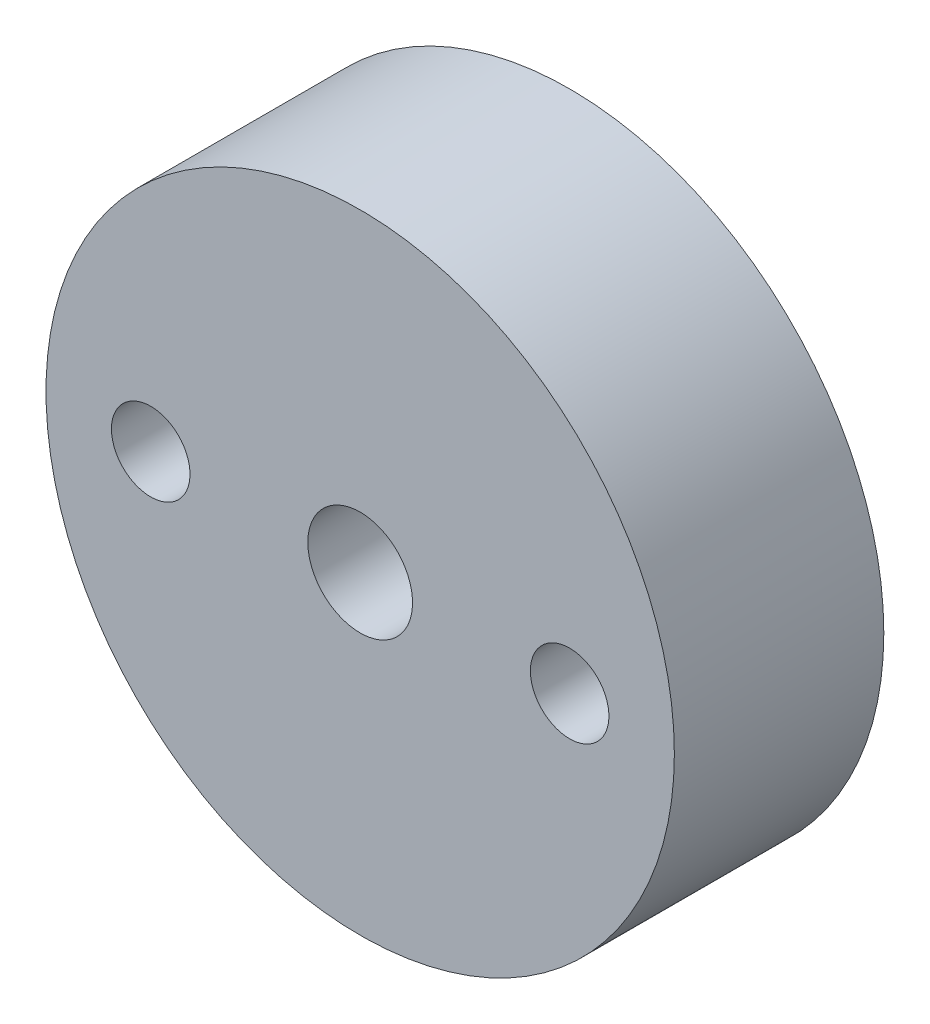
SolidWorks part; units mm, degrees
ref_plane "Front Plane" through (0, 0, 0) normal (0, 0, 1) x (1, 0, 0)
ref_plane "Top Plane" through (0, 0, 0) normal (0, 1, 0) x (1, 0, 0)
ref_plane "Right Plane" through (0, 0, 0) normal (1, 0, 0) x (0, 0, -1)
sketch "Sketch1" plane through (0, 0, 0) normal (0, 0, 1) x (1, 0, 0)
  circle A0 centre (0, 0) radius 38.1
  dimension "D1" = 76.2
extrude "OD Don't Care" add sketch "Sketch1" along normal blind 25.4
sketch "Sketch2" plane through (0, 0, 0) normal (0, 0, -1) x (-1, 0, 0)
  line L0 (-25.4, 0) -> (0, 0) construction
  line L1 (0, 0) -> (25.4, 0) construction
  circle A0 centre (-25.4, 0) radius 4.7625
  circle A1 centre (25.4, 0) radius 4.7625
  dimension "D1" = 9.525
  dimension "D2" = 25.4
extrude "3/8\"-16 Tapped Holes" cut sketch "Sketch2" against normal through all
sketch "Sketch4" plane through (0, 0, 0) normal (0, 0, -1) x (-1, 0, 0)
  circle A0 centre (0, 0) radius 6.35
  dimension "D1" = 12.7
extrude "1/2\"-13 Tapped Hole" cut sketch "Sketch4" against normal through all
